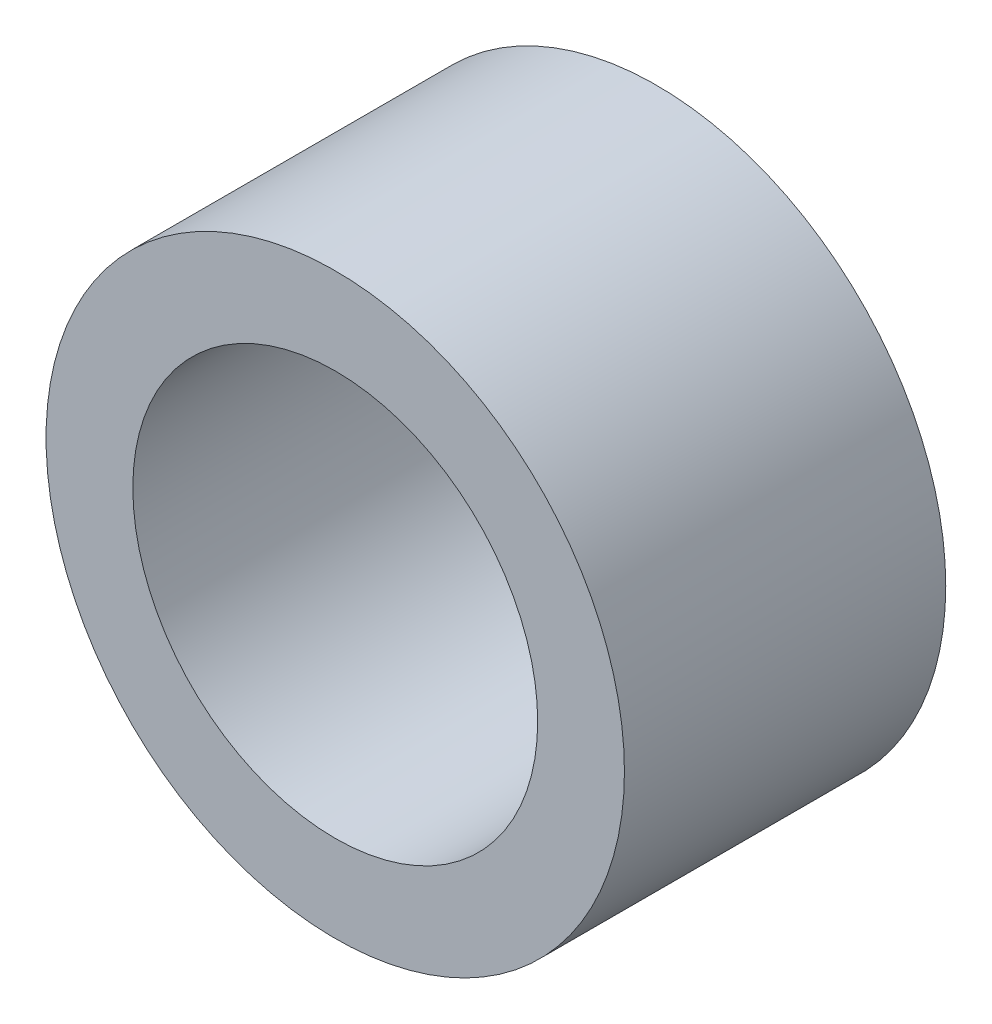
SolidWorks part; units mm, degrees
ref_plane "Front Plane" through (0, 0, 0) normal (0, 0, 1) x (1, 0, 0)
ref_plane "Top Plane" through (0, 0, 0) normal (0, 1, 0) x (1, 0, 0)
ref_plane "Right Plane" through (0, 0, 0) normal (1, 0, 0) x (0, 0, -1)
sketch "Sketch1" plane through (0, 0, 0) normal (0, 0, 1) x (1, 0, 0)
  circle A0 centre (0, 0) radius 3.15
  circle A1 centre (0, 0) radius 4.5
  dimension "D1" = 6.3
  dimension "D2" = 9
extrude "Boss-Extrude1" add sketch "Sketch1" along normal blind 5
